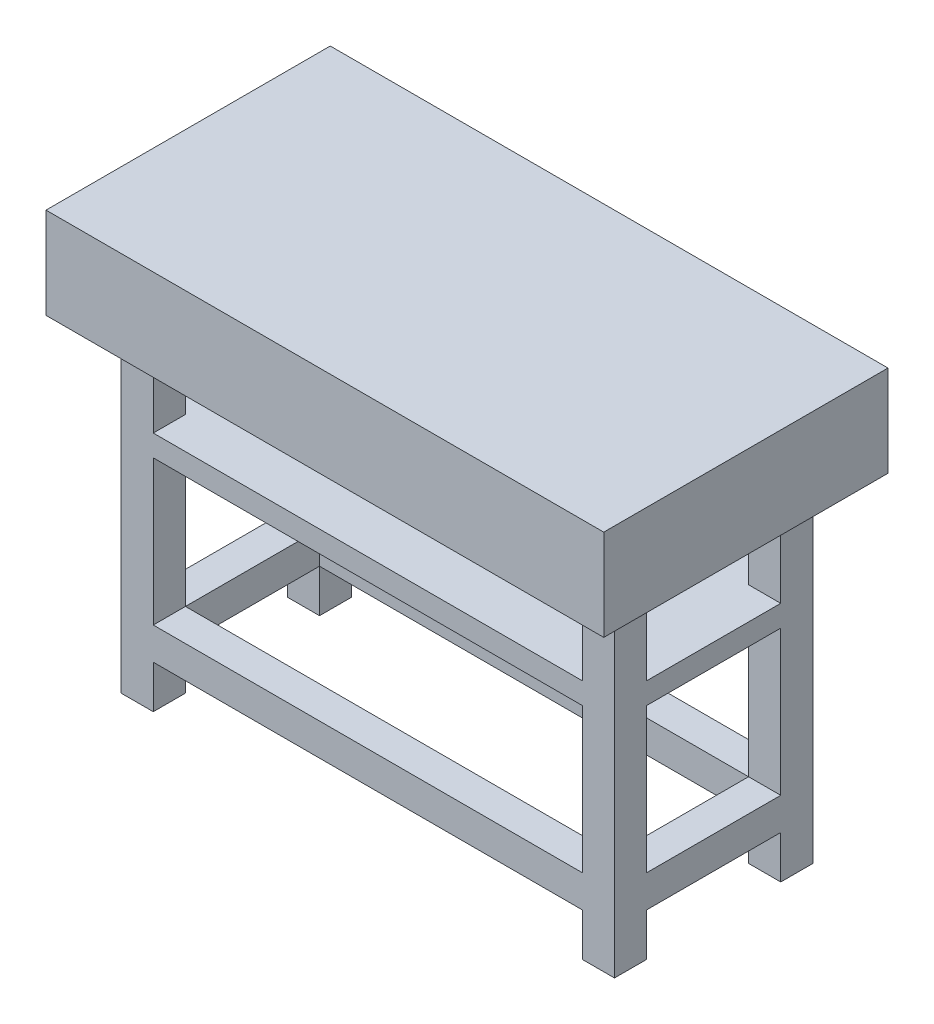
SolidWorks part; units mm, degrees
ref_plane "正面" through (0, 0, 0) normal (0, 0, 1) x (1, 0, 0)
ref_plane "平面" through (0, 0, 0) normal (0, 1, 0) x (1, 0, 0)
ref_plane "右側面" through (0, 0, 0) normal (1, 0, 0) x (0, 0, -1)
sketch "ｽｹｯﾁ2" plane through (0, 0, 0) normal (0, 1, 0) x (1, 0, 0)
  line L1 (0, 0) -> (1040, 0)
  line L2 (0, 0) -> (0, 530)
  line L3 (0, 530) -> (1040, 530)
  line L4 (1040, 0) -> (1040, 530)
  dimension "D1" = 1040
  dimension "D2" = 530
extrude "ﾎﾞｽ - 押し出し1" add sketch "ｽｹｯﾁ2" along normal blind 170
sketch "ｽｹｯﾁ3" plane through (0, 0, 0) normal (0, -1, 0) x (-1, 0, 0)
  line L0 (0, 530) -> (0, 0) construction
  line L1 (-980, 60) -> (-920, 60)
  line L2 (-980, 60) -> (-980, 470)
  line L3 (-980, 470) -> (-920, 470)
  line L4 (-920, 60) -> (-920, 470)
  line L5 (-120, 60) -> (-60, 60)
  line L6 (-120, 60) -> (-120, 470)
  line L7 (-120, 470) -> (-60, 470)
  line L8 (-60, 60) -> (-60, 470)
  line L9 (-1040, 530) -> (0, 530) construction
  line L10 (0, 0) -> (-1040, 0) construction
  line L11 (-1040, 0) -> (-1040, 530) construction
  line L13 (-920, 450) -> (-120, 450)
  line L14 (-920, 450) -> (-920, 390)
  line L15 (-920, 390) -> (-120, 390)
  line L16 (-120, 450) -> (-120, 390)
  line L17 (-120, 80) -> (-920, 80)
  line L18 (-120, 80) -> (-120, 140)
  line L19 (-120, 140) -> (-920, 140)
  line L20 (-920, 80) -> (-920, 140)
  dimension "D1" = 60
  dimension "D2" = 60
  dimension "D3" = 60
  dimension "D4" = 60
  dimension "D5" = 60
  dimension "D6" = 60
  dimension "D7" = 60
  dimension "D8" = 60
  dimension "D9" = 60
  dimension "D10" = 60
  dimension "D11" = 20
  dimension "D12" = 20
extrude "ﾎﾞｽ - 押し出し2" add sketch "ｽｹｯﾁ3" along normal blind 60 contours L4 L15 L6 L13 | L1 L4 L3 L2 | L6 L19 L4 L17 | L5 L8 L7 L6
sketch "ｽｹｯﾁ4" plane through (0, -60, 0) normal (0, -1, 0) x (-1, 0, 0)
  line L1 (-920, 390) -> (-980, 390)
  line L2 (-920, 390) -> (-920, 450)
  line L3 (-920, 450) -> (-980, 450)
  line L4 (-980, 390) -> (-980, 450)
  line L5 (-920, 140) -> (-980, 140)
  line L6 (-920, 140) -> (-920, 80)
  line L7 (-920, 80) -> (-980, 80)
  line L8 (-980, 140) -> (-980, 80)
  line L9 (-120, 390) -> (-60, 390)
  line L10 (-120, 390) -> (-120, 450)
  line L11 (-120, 450) -> (-60, 450)
  line L12 (-60, 390) -> (-60, 450)
  line L13 (-120, 140) -> (-60, 140)
  line L14 (-120, 140) -> (-120, 80)
  line L15 (-120, 80) -> (-60, 80)
  line L16 (-60, 140) -> (-60, 80)
  dimension "D1" = 60
  dimension "D2" = 60
  dimension "D3" = 60
  dimension "D4" = 60
  dimension "D5" = 60
  dimension "D6" = 60
  dimension "D7" = 60
  dimension "D8" = 60
extrude "ﾎﾞｽ - 押し出し3" add sketch "ｽｹｯﾁ4" along normal blind 560
sketch "ｽｹｯﾁ5" plane through (0, 0, -140) normal (0, 0, -1) x (-1, 0, 0)
  line L0 (-120, -620) -> (-120, -60) construction
  line L1 (-120, -540) -> (-60, -540)
  line L2 (-120, -540) -> (-120, -480)
  line L3 (-120, -480) -> (-60, -480)
  line L4 (-60, -540) -> (-60, -480)
  line L5 (-60, -620) -> (-60, -60) construction
  line L6 (-980, -620) -> (-980, -60) construction
  line L7 (-980, -540) -> (-920, -540)
  line L8 (-980, -540) -> (-980, -480)
  line L9 (-980, -480) -> (-920, -480)
  line L10 (-920, -540) -> (-920, -480)
  line L11 (-920, -620) -> (-920, -60) construction
  line L12 (-60, -620) -> (-120, -620) construction
  line L13 (-920, -620) -> (-980, -620) construction
  line L15 (-980, -170) -> (-920, -170)
  line L16 (-980, -170) -> (-980, -210)
  line L17 (-980, -210) -> (-920, -210)
  line L18 (-920, -170) -> (-920, -210)
  line L19 (-120, -170) -> (-60, -170)
  line L20 (-120, -170) -> (-120, -210)
  line L21 (-120, -210) -> (-60, -210)
  line L22 (-60, -170) -> (-60, -210)
  dimension "D1" = 60
  dimension "D2" = 60
  dimension "D3" = 80
  dimension "D4" = 80
  dimension "D5" = 40
  dimension "D6" = 40
  dimension "D7" = 270
  dimension "D8" = 270
extrude "ﾎﾞｽ - 押し出し4" add sketch "ｽｹｯﾁ5" along normal up to next
sketch "ｽｹｯﾁ6" plane through (120, 0, 0) normal (1, 0, 0) x (0, 0, -1)
  line L1 (390, -540) -> (450, -540)
  line L2 (390, -540) -> (390, -480)
  line L3 (390, -480) -> (450, -480)
  line L4 (450, -540) -> (450, -480)
  line L5 (140, -540) -> (80, -540)
  line L6 (140, -540) -> (140, -480)
  line L7 (140, -480) -> (80, -480)
  line L8 (80, -540) -> (80, -480)
  dimension "D1" = 60
  dimension "D2" = 60
  dimension "D3" = 60
  dimension "D4" = 60
extrude "ﾎﾞｽ - 押し出し5" add sketch "ｽｹｯﾁ6" along normal up to next
sketch "ｽｹｯﾁ7" plane through (120, 0, 0) normal (1, 0, 0) x (0, 0, -1)
  line L0 (390, -210) -> (140, -210) construction
  line L1 (80, -170) -> (450, -170)
  line L2 (80, -170) -> (80, -210)
  line L3 (80, -210) -> (450, -210)
  line L4 (450, -170) -> (450, -210)
  line L5 (80, -480) -> (80, -60) construction
  line L6 (390, -170) -> (140, -170) construction
  line L7 (450, -480) -> (450, -60) construction
extrude "ﾎﾞｽ - 押し出し6" add sketch "ｽｹｯﾁ7" along normal up to next
